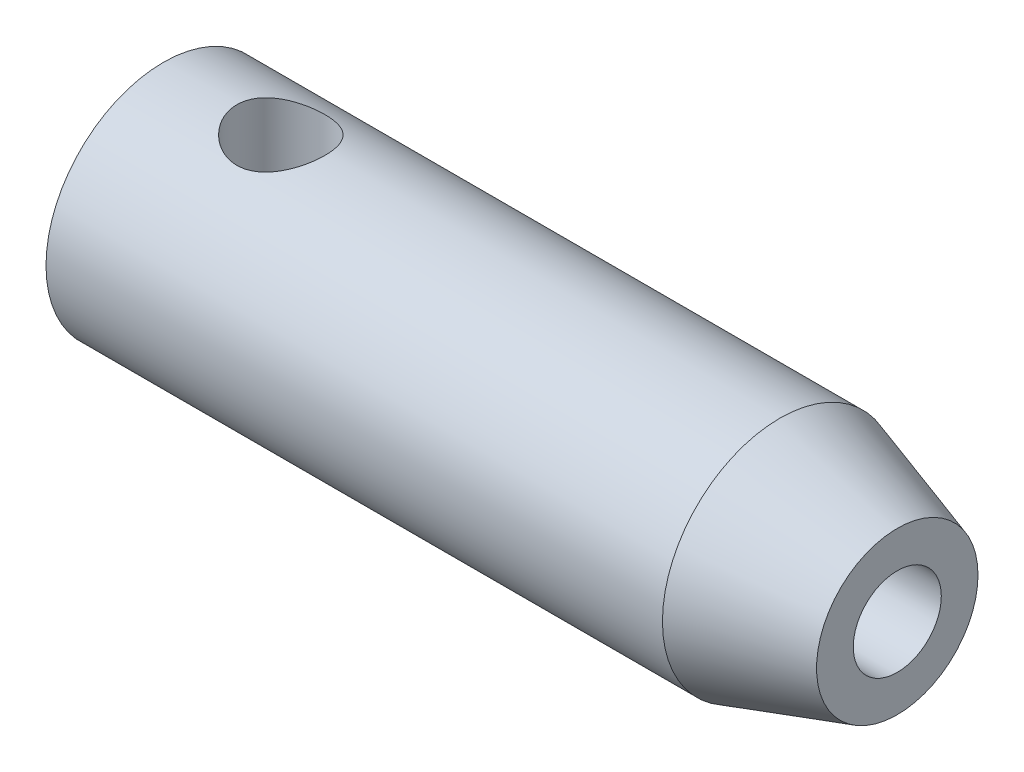
SolidWorks part; units mm, degrees
ref_plane "Front Plane" through (0, 0, 0) normal (0, 0, 1) x (1, 0, 0)
ref_plane "Top Plane" through (0, 0, 0) normal (0, 1, 0) x (1, 0, 0)
ref_plane "Right Plane" through (0, 0, 0) normal (1, 0, 0) x (0, 0, -1)
sketch "Sketch1" plane through (0, 0, 0) normal (0, 0, 1) x (1, 0, 0)
  line L0 (0, 0) -> (0, 4)
  line L3 (25, 0) -> (0, 0)
  line L4 (25, 0) -> (25, 2.75)
  line L5 (25, 0) -> (21, 0)
  line L6 (21, 0) -> (21, 4)
  line L7 (21, 4) -> (25, 2.75)
  line L8 (0, 4) -> (21, 4)
  dimension "D1" = 4
  dimension "D2" = 2.75
  dimension "D3" = 25
revolve "Revolve1" add sketch "Sketch1" angle 360 about L3
sketch "Sketch2" plane through (0, 0, 0) normal (1, 0, 0) x (0, 0, -1)
  circle A0 centre (0, 0) radius 1.5
extrude "Extrude4" cut sketch "Sketch2" along normal through all
sketch "Sketch3" plane through (0, 0, 0) normal (0, 1, 0) x (1, 0, 0)
  line L0 (0, 0) -> (4, 0)
  circle A0 centre (4, 0) radius 1.5
  dimension "D2" = 3
  dimension "D1" = 4
extrude "Extrude5" cut sketch "Sketch3" along normal blind 10
